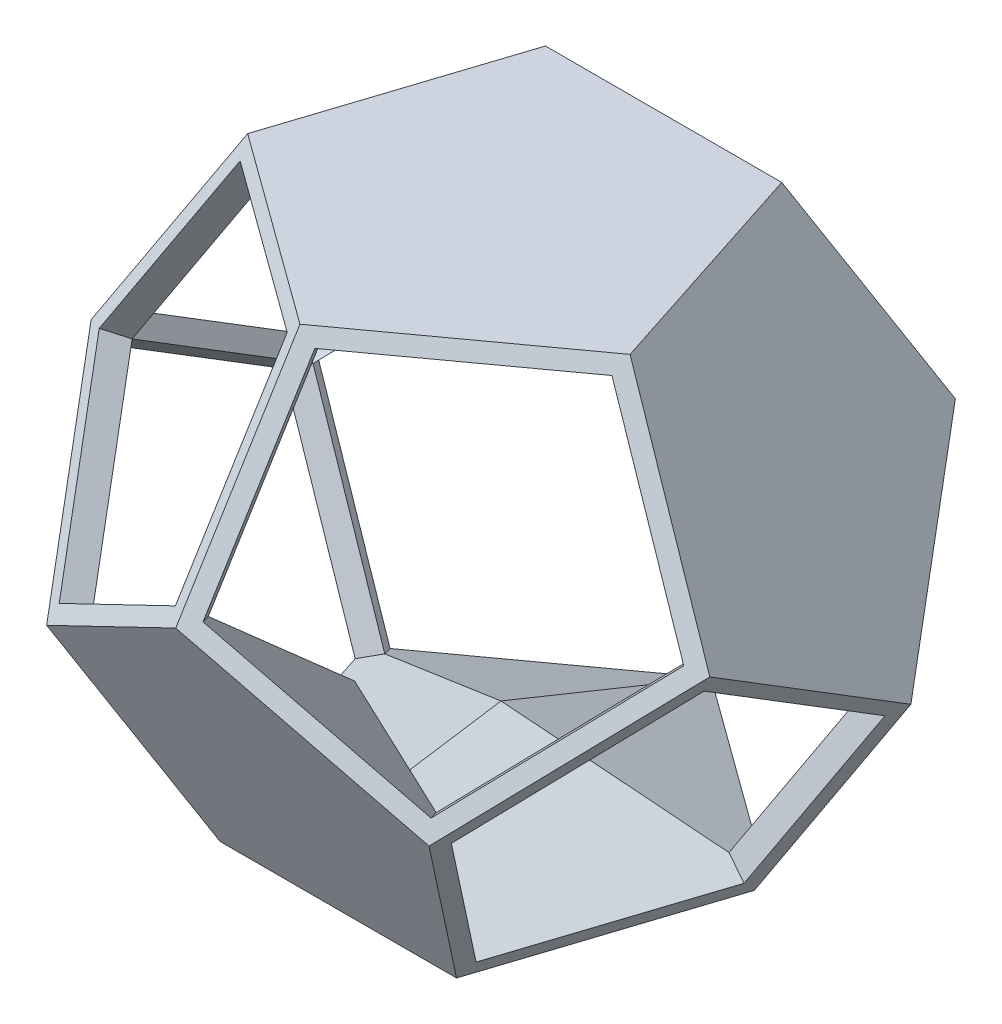
SolidWorks part; units mm, degrees
ref_plane "Front Plane" through (0, 0, 0) normal (0, 0, 1) x (1, 0, 0)
ref_plane "Top Plane" through (0, 0, 0) normal (0, 1, 0) x (1, 0, 0)
ref_plane "Right Plane" through (0, 0, 0) normal (1, 0, 0) x (0, 0, -1)
sketch "Sketch1" plane through (0, 0, 0) normal (0, 1, 0) x (1, 0, 0)
  line L6 (0, 50) -> (-47.5528, 15.4508)
  line L7 (-47.5528, 15.4508) -> (-29.3893, -40.4508)
  line L8 (-29.3893, -40.4508) -> (29.3893, -40.4508)
  line L9 (29.3893, -40.4508) -> (47.5528, 15.4508)
  line L10 (47.5528, 15.4508) -> (0, 50)
  circle A0 centre (0, 0) radius 50 construction
  dimension "D1" = 100
extrude "creation_extrude" add sketch "Sketch1" along normal blind 130.9017 draft 26.565 contours L6 L7 L8 L9 L10
sketch "Sketch2" plane through (0, 130.9017, 0) normal (0, 1, 0) x (1, 0, 0)
  line L1 (0, -50) -> (47.5528, -15.4508)
  line L2 (47.5528, -15.4508) -> (29.3893, 40.4508)
  line L3 (29.3893, 40.4508) -> (-29.3893, 40.4508)
  line L4 (-29.3893, 40.4508) -> (-47.5528, -15.4508)
  line L5 (-47.5528, -15.4508) -> (0, -50)
  circle A0 centre (0, 0) radius 50 construction
  dimension "D1" = 100
extrude "creation_cut" cut sketch "Sketch2" against normal blind 130.9017 draft 26.565 flip side to cut
sketch "Sketch3" plane through (0, 130.9017, 0) normal (0, 1, 0) x (1, 0, 0)
  line L1 (0, -45) -> (42.7975, -13.9058)
  line L2 (42.7975, -13.9058) -> (26.4503, 36.4058)
  line L3 (26.4503, 36.4058) -> (-26.4503, 36.4058)
  line L4 (-26.4503, 36.4058) -> (-42.7975, -13.9058)
  line L5 (-42.7975, -13.9058) -> (0, -45)
  circle A0 centre (0, 0) radius 45 construction
  dimension "D1" = 90
extrude "A" [suppressed] cut sketch "Sketch3" against normal blind 25.4
sketch "Sketch4" plane through (0, 0, 0) normal (0, -1, 0) x (1, 0, 0)
  line L1 (0, -45) -> (42.7975, -13.9058)
  line L2 (42.7975, -13.9058) -> (26.4503, 36.4058)
  line L3 (26.4503, 36.4058) -> (-26.4503, 36.4058)
  line L4 (-26.4503, 36.4058) -> (-42.7975, -13.9058)
  line L5 (-42.7975, -13.9058) -> (0, -45)
  circle A0 centre (0, 0) radius 45 construction
  dimension "D1" = 90
extrude "A_inv" [suppressed] cut sketch "Sketch4" against normal blind 25.4
sketch "Sketch5" plane through (0, 42.3607, -84.7214) normal (0, 0.4472, -0.8944) x (-1, 0, 0)
  line L0 (0, 58.541) -> (-47.5528, 43.0902) construction
  line L2 (-42.7975, 44.6353) -> (0, 13.541)
  line L3 (0, 13.541) -> (42.7975, 44.6353)
  line L4 (42.7975, 44.6353) -> (26.4503, 94.9468)
  line L5 (26.4503, 94.9468) -> (-26.4503, 94.9468)
  line L6 (-26.4503, 94.9468) -> (-42.7975, 44.6353)
  circle A0 centre (0, 58.541) radius 50 construction
  circle A1 centre (0, 58.541) radius 45 construction
  dimension "D1" = 90
extrude "B" cut sketch "Sketch5" against normal blind 50.8
sketch "Sketch6" plane through (0, -16.1803, 32.3607) normal (0, -0.4472, 0.8944) x (1, 0, 0)
  line L0 (0, 58.541) -> (-47.5528, 73.9919) construction
  line L2 (-42.7975, 72.4468) -> (-26.4503, 22.1353)
  line L3 (-26.4503, 22.1353) -> (26.4503, 22.1353)
  line L4 (26.4503, 22.1353) -> (42.7975, 72.4468)
  line L5 (42.7975, 72.4468) -> (0, 103.541)
  line L6 (0, 103.541) -> (-42.7975, 72.4468)
  circle A0 centre (0, 58.541) radius 50 construction
  circle A1 centre (0, 58.541) radius 45 construction
  dimension "D1" = 90
extrude "B_inv" [suppressed] cut sketch "Sketch6" against normal blind 25.4
sketch "Sketch7" plane through (80.5748, 42.3607, -26.1803) normal (0.8507, 0.4472, -0.2764) x (-0.2446, -0.1286, -0.961)
  line L0 (-8.4181, 57.9326) -> (40.8623, 49.4804) construction
  line L2 (35.9343, 50.3256) -> (12.5223, 97.7635)
  line L3 (12.5223, 97.7635) -> (-39.8286, 90.1565)
  line L4 (-39.8286, 90.1565) -> (-48.7712, 38.0171)
  line L5 (-48.7712, 38.0171) -> (-1.9472, 13.4003)
  line L6 (-1.9472, 13.4003) -> (35.9343, 50.3256)
  circle A0 centre (-8.4181, 57.9326) radius 50 construction
  circle A1 centre (-8.4181, 57.9326) radius 45 construction
  dimension "D1" = 90
extrude "C" [suppressed] cut sketch "Sketch7" against normal blind 25.4
sketch "Sketch8" plane through (-30.7768, -16.1803, 10) normal (-0.8507, -0.4472, 0.2764) x (0.2446, 0.1286, 0.961)
  line L0 (8.4181, 57.9326) -> (-36.4187, 80.0609) construction
  line L2 (-31.935, 77.8481) -> (-22.9924, 25.7087)
  line L3 (-22.9924, 25.7087) -> (29.3585, 18.1017)
  line L4 (29.3585, 18.1017) -> (52.7705, 65.5396)
  line L5 (52.7705, 65.5396) -> (14.889, 102.4649)
  line L6 (14.889, 102.4649) -> (-31.935, 77.8481)
  circle A0 centre (8.4181, 57.9326) radius 50 construction
  circle A1 centre (8.4181, 57.9326) radius 45 construction
  dimension "D1" = 90
extrude "C_inv" cut sketch "Sketch8" against normal blind 50.8
sketch "Sketch9" plane through (49.798, 42.3607, 68.541) normal (0.5257, 0.4472, 0.7236) x (0.8507, -0.2764, -0.4472)
  line L0 (-18.0902, 55.6758) -> (-2.6393, 103.2286) construction
  line L2 (-4.1844, 98.4734) -> (-54.4959, 82.1262)
  line L3 (-54.4959, 82.1262) -> (-54.4959, 29.2255)
  line L4 (-54.4959, 29.2255) -> (-4.1844, 12.8783)
  line L5 (-4.1844, 12.8783) -> (26.9098, 55.6758)
  line L6 (26.9098, 55.6758) -> (-4.1844, 98.4734)
  circle A0 centre (-18.0902, 55.6758) radius 50 construction
  circle A1 centre (-18.0902, 55.6758) radius 45 construction
  dimension "D1" = 90
extrude "D" cut sketch "Sketch9" against normal blind 50.8
sketch "Sketch10" plane through (-19.0211, -16.1803, -26.1803) normal (-0.5257, -0.4472, -0.7236) x (-0.8507, 0.2764, 0.4472)
  line L0 (18.0902, 55.6758) -> (33.541, 103.2286) construction
  line L2 (31.9959, 98.4734) -> (-18.3156, 82.1262)
  line L3 (-18.3156, 82.1262) -> (-18.3156, 29.2255)
  line L4 (-18.3156, 29.2255) -> (31.9959, 12.8783)
  line L5 (31.9959, 12.8783) -> (63.0902, 55.6758)
  line L6 (63.0902, 55.6758) -> (31.9959, 98.4734)
  circle A0 centre (18.0902, 55.6758) radius 50 construction
  circle A1 centre (18.0902, 55.6758) radius 45 construction
  dimension "D1" = 90
extrude "D_inv" cut sketch "Sketch10" against normal blind 50.8
sketch "Sketch11" plane through (-49.798, 42.3607, 68.541) normal (-0.5257, 0.4472, 0.7236) x (0.8507, 0.2764, 0.4472)
  line L0 (18.0902, 55.6758) -> (2.6393, 103.2286) construction
  line L2 (4.1844, 98.4734) -> (-26.9098, 55.6758)
  line L3 (-26.9098, 55.6758) -> (4.1844, 12.8783)
  line L4 (4.1844, 12.8783) -> (54.4959, 29.2255)
  line L5 (54.4959, 29.2255) -> (54.4959, 82.1262)
  line L6 (54.4959, 82.1262) -> (4.1844, 98.4734)
  circle A0 centre (18.0902, 55.6758) radius 50 construction
  circle A1 centre (18.0902, 55.6758) radius 45 construction
  dimension "D1" = 90
extrude "E" cut sketch "Sketch11" against normal blind 50.8
sketch "Sketch12" plane through (19.0211, -16.1803, -26.1803) normal (0.5257, -0.4472, -0.7236) x (-0.8507, -0.2764, -0.4472)
  line L0 (-18.0902, 55.6758) -> (-33.541, 103.2286) construction
  line L2 (-31.9959, 98.4734) -> (-63.0902, 55.6758)
  line L3 (-63.0902, 55.6758) -> (-31.9959, 12.8783)
  line L4 (-31.9959, 12.8783) -> (18.3156, 29.2255)
  line L5 (18.3156, 29.2255) -> (18.3156, 82.1262)
  line L6 (18.3156, 82.1262) -> (-31.9959, 98.4734)
  circle A0 centre (-18.0902, 55.6758) radius 50 construction
  circle A1 centre (-18.0902, 55.6758) radius 45 construction
  dimension "D1" = 90
extrude "E_inv" cut sketch "Sketch12" against normal blind 50.8
sketch "Sketch13" plane through (-80.5748, 42.3607, -26.1803) normal (-0.8507, 0.4472, -0.2764) x (-0.2446, 0.1286, 0.961)
  line L0 (8.4181, 57.9326) -> (-14.849, 102.1892) construction
  line L2 (-12.5223, 97.7635) -> (-35.9343, 50.3256)
  line L3 (-35.9343, 50.3256) -> (1.9472, 13.4003)
  line L4 (1.9472, 13.4003) -> (48.7712, 38.0171)
  line L5 (48.7712, 38.0171) -> (39.8286, 90.1565)
  line L6 (39.8286, 90.1565) -> (-12.5223, 97.7635)
  circle A0 centre (8.4181, 57.9326) radius 50 construction
  circle A1 centre (8.4181, 57.9326) radius 45 construction
  dimension "D1" = 90
extrude "F" cut sketch "Sketch13" against normal blind 50.8
sketch "Sketch14" plane through (30.7768, -16.1803, 10) normal (0.8507, -0.4472, 0.2764) x (0.2446, -0.1286, -0.961)
  line L0 (-8.4181, 57.9326) -> (-31.6852, 13.676) construction
  line L2 (-29.3585, 18.1017) -> (22.9924, 25.7087)
  line L3 (22.9924, 25.7087) -> (31.935, 77.8481)
  line L4 (31.935, 77.8481) -> (-14.889, 102.4649)
  line L5 (-14.889, 102.4649) -> (-52.7705, 65.5396)
  line L6 (-52.7705, 65.5396) -> (-29.3585, 18.1017)
  circle A0 centre (-8.4181, 57.9326) radius 50 construction
  circle A1 centre (-8.4181, 57.9326) radius 45 construction
  dimension "D1" = 90
extrude "F_inv" cut sketch "Sketch14" against normal blind 50.8
equation "\"ratio\"= ( sin ( 18 ) + 1 ) 'ratio base:height"
equation "\"height\"= \"base\" * \"ratio\"'height of extrude"
equation "\"D1@Sketch1\" = \"base\""
equation "\"D1@Sketch2\"= \"D1@Sketch1\""
equation "\"D1@creation_cut\"= \"height\""
equation "\"D1@creation_extrude\"= \"height\""
equation "\"base\"= 10cm"
equation "\"D1@Sketch3\" = \"base\" * \"thick\""
equation "\"thick\"= 0.9"
equation "\"D1@Sketch4\"= \"base\" * \"thick\""
equation "\"D1@Sketch5\"= \"base\" * \"thick\""
equation "\"D1@Sketch6\"= \"base\" * \"thick\""
equation "\"D1@Sketch7\"= \"base\" * \"thick\""
equation "\"D1@Sketch8\"= \"base\" * \"thick\""
equation "\"D1@Sketch9\"= \"base\" * \"thick\""
equation "\"D1@Sketch10\"= \"base\" * \"thick\""
equation "\"D1@Sketch11\"= \"base\" * \"thick\""
equation "\"D1@Sketch12\"= \"base\" * \"thick\""
equation "\"D1@Sketch13\"= \"base\" * \"thick\""
equation "\"D1@Sketch14\"= \"base\" * \"thick\""
